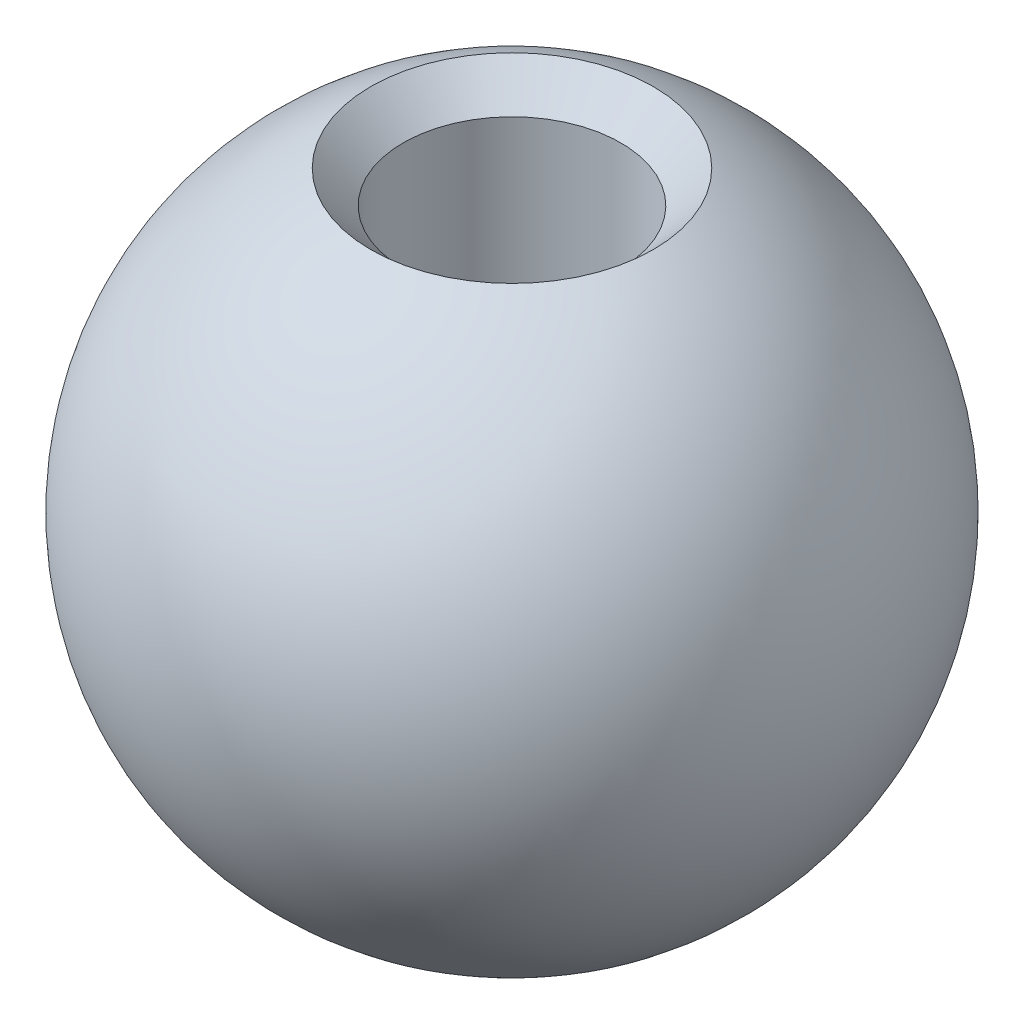
SolidWorks part; units mm, degrees
ref_plane "前视基准面" through (0, 0, 0) normal (0, 0, 1) x (1, 0, 0)
ref_plane "上视基准面" through (0, 0, 0) normal (0, 1, 0) x (1, 0, 0)
ref_plane "右视基准面" through (0, 0, 0) normal (1, 0, 0) x (0, 0, -1)
sketch "草图1" plane through (0, 0, 0) normal (0, 0, 1) x (1, 0, 0)
  line L0 (0, 0) -> (0, 8.5356) construction
  line L1 (0, 5) -> (0, -5)
  arc A0 (0, -5) -> (0, 5) centre (0, 0) ccw
  dimension "D1" = 10
revolve "旋转1" add sketch "草图1" angle 360 about L0
ref_plane "基准面1" through (0, 5, 0) normal (0, 1, 0) x (1, 0, 0)
hole_wizard "M4 螺纹孔1" positions "草图3" profile "草图5" tap size "M4" standard "GB"
sketch "草图3" plane through (0, 5, 0) normal (0, 1, 0) x (1, 0, 0)
  point P0 (0, 0)
sketch "草图5" plane through (0, 5, 0) normal (1, 0, 0) x (0, 0, 1)
  line L0 (0, 0) -> (0, 7.9914)
  line L1 (0, 7.9914) -> (1.65, 7)
  line L2 (1.65, 7) -> (1.65, 0.975)
  line L3 (1.65, 0.975) -> (2.625, 0)
  line L5 (2.625, 0) -> (0, 0)
  line L6 (-1.65, 0.975) -> (-2.625, 0) construction
  line L10 (0, 7.9914) -> (-1.65, 7) construction
  line L11 (0, -6.35) -> (0, 107.95) construction
  dimension "螺纹孔钻头直径" = 3.3
  dimension "螺纹孔钻头深度" = 7
  dimension "近端锥形沉头孔直径" = 5.25
  dimension "近端锥形沉头孔角度" = 90
  dimension "导头角度" = 118
cosmetic thread "孔螺蚊线3" parameters "D1"=7, "D2"=4
